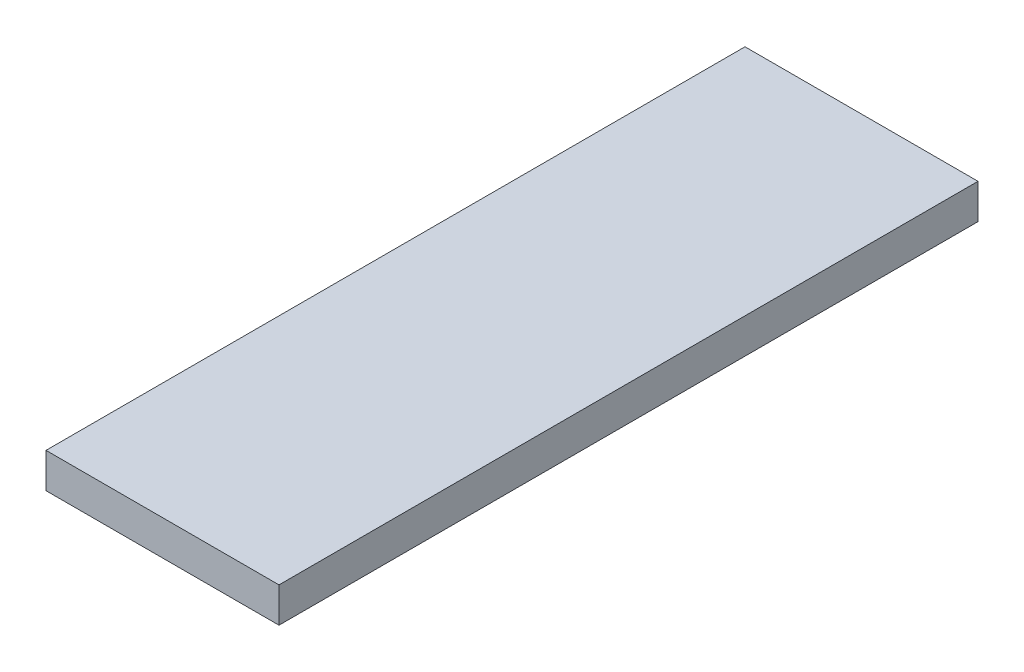
SolidWorks part; units mm, degrees
material "6061 Alloy"
ref_plane "Front Plane" through (0, 0, 0) normal (0, 0, 1) x (1, 0, 0)
ref_plane "Top Plane" through (0, 0, 0) normal (0, 1, 0) x (1, 0, 0)
ref_plane "Right Plane" through (0, 0, 0) normal (1, 0, 0) x (0, 0, -1)
sketch "Sketch1" plane through (0, 0, 0) normal (0, 0, 1) x (1, 0, 0)
  line L0 (0, 0) -> (0, -3)
  line L1 (0, -3) -> (20, -3)
  line L2 (0, 0) -> (20, 0)
  line L3 (20, 0) -> (20, -3)
  dimension "D1" = 20
  dimension "D2" = 3
extrude "Boss-Extrude1" add sketch "Sketch1" along normal blind 60
